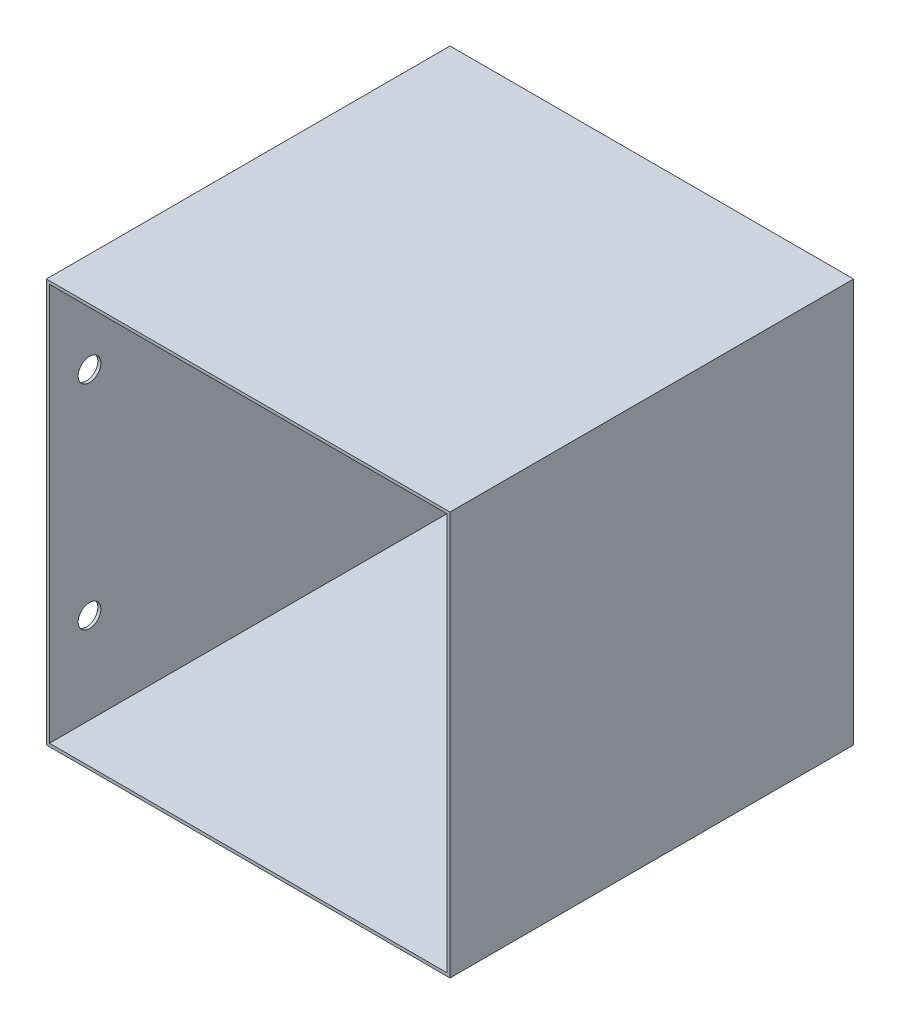
SolidWorks part; units mm, degrees
material "AISI 304"
ref_plane "Alzado" through (0, 0, 0) normal (0, 0, 1) x (1, 0, 0)
ref_plane "Planta" through (0, 0, 0) normal (0, 1, 0) x (1, 0, 0)
ref_plane "Vista lateral" through (0, 0, 0) normal (1, 0, 0) x (0, 0, -1)
sketch "Croquis1" plane through (0, 0, 0) normal (0, 0, 1) x (1, 0, 0)
  line L1 (0, 0) -> (80, 0)
  line L2 (0, 0) -> (0, 80)
  line L3 (0, 80) -> (80, 80)
  line L4 (80, 0) -> (80, 80)
  dimension "D1" = 80
  dimension "D2" = 80
extrude "Saliente-Extruir1" add sketch "Croquis1" along normal blind 80
shell "Vaciado1" thickness 0.6
hole_wizard "Taladro de margen para M41" positions "Croquis2" profile "Croquis3" hole size "M4" standard "ISO"
sketch "Croquis2" plane through (0, -79.6371, 0) normal (-1, 0, 0) x (0, 1, 0)
  point P0 (98.189, -72.0625)
  point P2 (140.4294, -72.0625)
  point P8 (0, 0)
sketch "Croquis3" plane through (0, 18.5518, 72.0625) normal (0, 1, 0) x (0, 0, 1)
  line L0 (0, 0) -> (0, 5)
  line L1 (0, 5) -> (2.25, 5)
  line L2 (2.25, 5) -> (2.25, 0)
  line L5 (2.25, 0) -> (0, 0)
  line L11 (0, -6.35) -> (0, 107.95) construction
  dimension "Diámetro de taladro hasta el siguiente" = 4.5
  dimension "Profundidad de taladro hasta el siguiente" = 5
